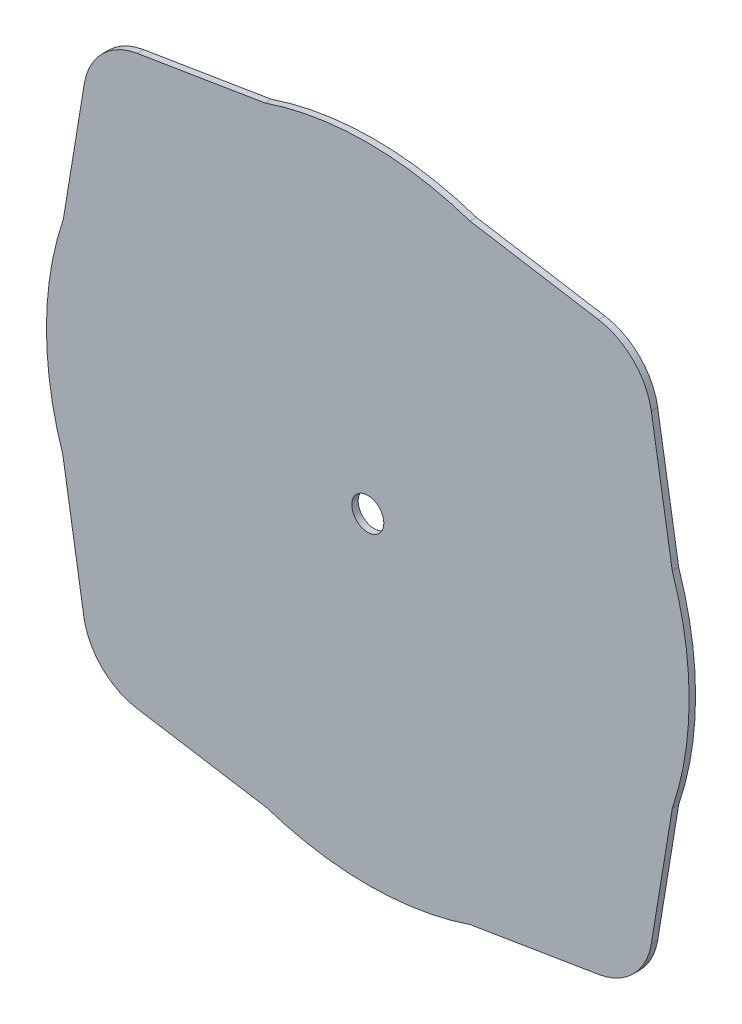
SolidWorks part; units mm, degrees
ref_plane "Front Plane" through (0, 0, 0) normal (0, 0, 1) x (1, 0, 0)
ref_plane "Top Plane" through (0, 0, 0) normal (0, 1, 0) x (1, 0, 0)
ref_plane "Right Plane" through (0, 0, 0) normal (1, 0, 0) x (0, 0, -1)
sketch "Sketch1" plane through (0, 0, 0) normal (0, 0, 1) x (1, 0, 0)
  line L882 (165.388, -217.9441) -> (129.467, -182.023) construction
  line L883 (165.388, 291.7862) -> (-344.3422, 291.7862) construction
  line L884 (165.388, 291.7862) -> (165.388, -217.9441) construction
  line L885 (165.388, -217.9441) -> (-344.3422, -217.9441) construction
  line L886 (-344.3422, 291.7862) -> (-344.3422, -217.9441) construction
  line L887 (165.388, 291.7862) -> (-344.3422, -217.9441) construction
  line L888 (165.388, -217.9441) -> (-344.3422, 291.7862) construction
  line L889 (-89.4771, -217.9441) -> (129.467, -182.023) construction
  line L890 (129.467, -182.023) -> (165.388, 36.9211) construction
  line L891 (93.4679, -187.9292) -> (-8.0403, -204.5832)
  line L892 (135.3732, -146.024) -> (152.0271, -44.5157)
  line L893 (-344.3422, -217.9441) -> (-308.8254, -182.4273) construction
  line L894 (-89.4771, -217.9441) -> (-272.655, -188.284) construction
  line L895 (-314.6821, -146.2569) -> (-344.3422, 36.9211) construction
  line L896 (-169.9038, -204.9214) -> (-272.655, -188.284)
  line L897 (-314.6821, -146.2569) -> (-331.3196, -43.5056)
  line L898 (-344.3422, 291.7862) -> (-308.4212, 255.8652) construction
  line L899 (-314.3298, 219.8511) -> (-344.3422, 36.9211) construction
  line L900 (-272.4048, 261.7596) -> (-88.9487, 291.7839) construction
  line L901 (-272.4048, 261.7596) -> (-171.2337, 278.3172)
  line L902 (-314.3298, 219.8511) -> (-330.9813, 118.3578)
  line L903 (165.388, 291.7862) -> (129.467, 255.8652) construction
  line L904 (135.3709, 219.8804) -> (165.388, 36.9211) construction
  line L905 (93.4844, 261.7825) -> (-88.9487, 291.7839) construction
  line L906 (93.4844, 261.7825) -> (-8.3492, 278.5292)
  line L907 (135.3709, 219.8804) -> (152.0271, 118.3578)
  arc A0 (152.0271, -44.5157) -> (152.0271, 118.3578) centre (-89.4771, 36.9211) ccw
  circle A1 centre (-89.4771, 36.9211) radius 12.7
  arc A2 (135.3732, -146.024) -> (93.4679, -187.9292) centre (85.2434, -137.7994) cw
  arc A3 (-314.6821, -146.2569) -> (-272.655, -188.284) centre (-264.5352, -138.1371) ccw
  arc A4 (-169.9038, -204.9214) -> (-8.0403, -204.5832) centre (-89.4771, 36.9211) ccw
  arc A5 (-314.3298, 219.8511) -> (-272.4048, 261.7596) centre (-264.2, 211.6265) cw
  arc A6 (-330.9813, 118.3578) -> (-331.3196, -43.5056) centre (-89.4771, 36.9211) ccw
  arc A7 (135.3709, 219.8804) -> (93.4844, 261.7825) centre (85.2411, 211.6558) ccw
  arc A8 (-8.3492, 278.5292) -> (-171.2337, 278.3172) centre (-89.4771, 36.9211) ccw
  dimension "D3" = 50.8
  dimension "D4" = 50.8
  dimension "D6" = 50.8
  dimension "D8" = 50.8
  dimension "D2" = 50.8
  dimension "D5" = 50.8
  dimension "D7" = 50.8
extrude "Boss-Extrude1" add sketch "Sketch1" along normal blind 5.08
scale "Scale1" scale about centroid uniform scaling yes scale factor 0.5
